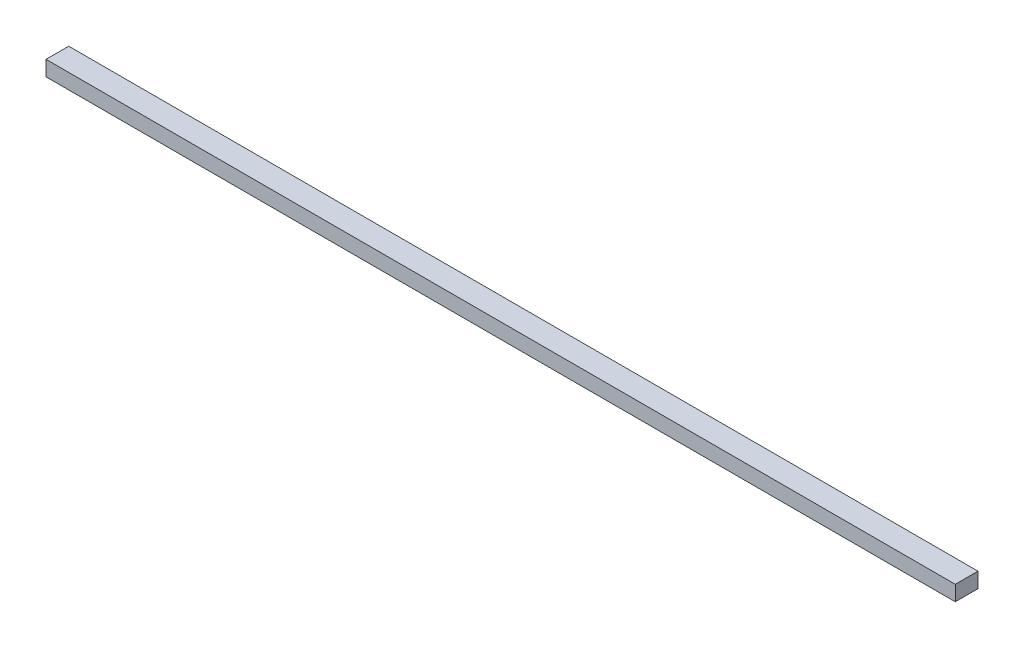
SolidWorks part; units mm, degrees
ref_plane "Front Plane" through (0, 0, 0) normal (0, 0, 1) x (1, 0, 0)
ref_plane "Top Plane" through (0, 0, 0) normal (0, 1, 0) x (1, 0, 0)
ref_plane "Right Plane" through (0, 0, 0) normal (1, 0, 0) x (0, 0, -1)
sketch "Sketch1" plane through (0, 0, 0) normal (0, 1, 0) x (1, 0, 0)
  line L1 (0, 0) -> (600, 0)
  line L2 (0, 0) -> (0, -15)
  line L3 (0, -15) -> (600, -15)
  line L4 (600, 0) -> (600, -15)
  dimension "D1" = 600
  dimension "D2" = 15
extrude "Boss-Extrude1" add sketch "Sketch1" along normal blind 10
